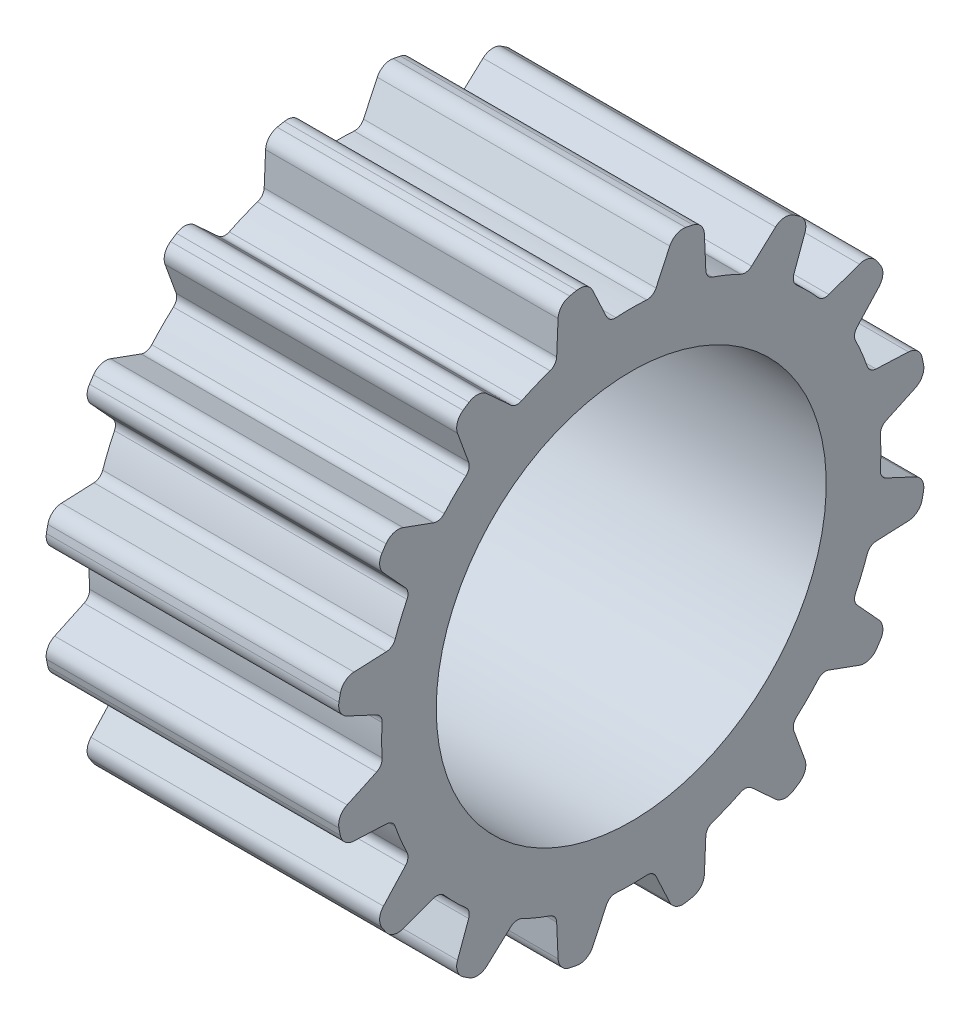
SolidWorks part; units mm, degrees
ref_plane "Front" through (0, 0, 0) normal (0, 0, 1) x (1, 0, 0)
ref_plane "Top" through (0, 0, 0) normal (0, 1, 0) x (1, 0, 0)
ref_plane "Right" through (0, 0, 0) normal (1, 0, 0) x (0, 0, -1)
sketch "Support-Cog" plane through (0, 0, 0) normal (1, 0, 0) x (0, 0, -1)
  line L0 (0, 0) -> (0, 6.1) construction
  line L3 (0.8861, 6.0353) -> (0.45, 5.1)
  line L4 (-0.8861, 6.0353) -> (-0.45, 5.1)
  line L5 (0.45, 5.1) -> (-0.45, 5.1) construction
  circle A1 centre (0, 0) radius 5.1198 construction
  circle A2 centre (0, 0) radius 6.1 construction
  arc A5 (0.7898, 5.8288) -> (1.1166, 5.9969) centre (1.0617, 5.702) cw
  arc A6 (-0.7898, 5.8288) -> (-1.1166, 5.9969) centre (-1.0617, 5.702) ccw
  circle A7 centre (0, 0) radius 4
  arc A8 (0.5084, 5.2252) -> (0.3148, 5.1101) centre (0.3271, 5.3097) cw
  arc A9 (-0.5084, 5.2252) -> (-0.3148, 5.1101) centre (-0.3271, 5.3097) ccw
  dimension "D1" = 50
  dimension "D2" = 0.9
  dimension "Diam-Gear" = 12.2
  dimension "Diam-Hole-Shaft" = 8
  dimension "D4" = 0.3
  dimension "D5" = 0.2
  dimension "D3" = 1
sketch "Support-Front" plane through (0, 0, 0) normal (0, 0, 1) x (1, 0, 0)
  line L0 (0, 0) -> (16, 0) construction
  line L1 (0, -4) -> (16, -4)
  line L2 (16, -8) -> (16, 8)
  line L3 (16, 8) -> (6, 8)
  line L4 (6, 8) -> (6, 6.1)
  line L5 (6, 6.1) -> (0, 6.1)
  line L6 (0, 6.1) -> (0, -6.1)
  line L7 (3, 6.1) -> (3, 0) construction
  line L8 (6, -6.1) -> (0, -6.1)
  line L9 (6, 8) -> (6, -8) construction
  line L10 (16, -8) -> (6, -8)
  line L11 (0, 6.1) -> (0, 8)
  line L12 (0, 4) -> (16, 4)
  line L13 (6, 6.1) -> (6, 8)
  line L14 (-0.3806, 7.8706) -> (0, 6.4501)
  line L15 (6, -8) -> (6, -6.1)
  line L16 (6, -6.1) -> (6, -8)
  line L17 (0, 6.4501) -> (0, 2.5423)
  line L18 (0.5, 2.5423) -> (0, 2.5423)
  line L19 (6, 2.5423) -> (6, 6.1)
  line L20 (0, -2.5423) -> (0, -6.1)
  line L21 (5.5, 6.5159) -> (5.5, 6.4501)
  line L22 (0, 2.5423) -> (0, 6.1)
  line L23 (6, -6.1) -> (6, -8)
  line L24 (6.3806, 7.8706) -> (5.8977, 8)
  line L25 (6, -8) -> (6, -6.1)
  line L26 (5.8977, 8) -> (5.5, 6.5159)
  line L27 (0.5, 2.5423) -> (0.5, 6.4501)
  line L28 (0.5, 6.4501) -> (0, 6.1) construction
  line L29 (6, 6.1) -> (6, 8)
  line L30 (0.5, 2.5423) -> (0, 6.1) construction
  line L31 (0, 6.4501) -> (0.5, 6.4501) construction
  line L34 (6, 6.4501) -> (5.5, 6.4501) construction
  line L35 (5.5, 2.5423) -> (5.5, 6.4501)
  line L36 (6, -2.5423) -> (6, -6.1)
  line L37 (6, 2.5423) -> (6, 6.1)
  line L38 (5.5, 2.5423) -> (6, 2.5423)
  line L39 (0.1023, 8) -> (0.5, 6.5159)
  line L40 (6, 6.4501) -> (6, 2.5423)
  line L41 (-0.3806, 7.8706) -> (0.1023, 8)
  line L42 (6.3806, 7.8706) -> (6, 6.4501)
  line L43 (6, 6.1) -> (6, 8)
  line L44 (0.5, -6.5159) -> (0.5, -6.4501)
  line L45 (6, -6.1) -> (6, -8)
  line L46 (6.3806, -7.8706) -> (6, -6.4501)
  line L47 (-0.3806, -7.8706) -> (0.1023, -8)
  line L48 (6, -6.4501) -> (6, -2.5423)
  line L49 (0.5, 6.5159) -> (0.5, 6.4501)
  line L50 (0.1023, -8) -> (0.5, -6.5159)
  line L51 (5.5, -2.5423) -> (6, -2.5423)
  line L52 (6, -2.5423) -> (6, -6.1)
  line L53 (5.5, -2.5423) -> (5.5, -6.4501)
  line L54 (6, -6.4501) -> (5.5, -6.4501) construction
  line L55 (0, -6.4501) -> (0.5, -6.4501) construction
  line L56 (6, -6.1) -> (6, -8)
  line L57 (0.5, -2.5423) -> (0.5, -6.4501)
  line L58 (5.8977, -8) -> (5.5, -6.5159)
  line L59 (6.3806, -7.8706) -> (5.8977, -8)
  line L60 (0, -2.5423) -> (0, -6.1)
  line L61 (5.5, -6.5159) -> (5.5, -6.4501)
  line L62 (6, -2.5423) -> (6, -6.1)
  line L63 (0.5, -2.5423) -> (0, -2.5423)
  line L64 (0, -6.4501) -> (0, -2.5423)
  line L65 (-0.3806, -7.8706) -> (0, -6.4501)
  line L66 (6, -6.1) -> (6, -8)
  line L67 (0, -6.1) -> (0, -8)
  line L68 (6, -6.1) -> (0, -6.1)
  line L69 (6, -8) -> (6, -6.1)
  line L70 (0, 6.4501) -> (0.5, 6.5159) construction
  dimension "D1" = 55
  dimension "Diam-Hub" = 16
  dimension "D2" = 8
  dimension "D3" = 15
  dimension "Width-Total" = 16
  dimension "Width-Cog" = 6
  dimension "Thickn-Flange" = 0.5
  dimension "Diam-Flange" = 16
sketch "Support-Key" plane through (0, 0, 0) normal (1, 0, 0) x (0, 0, -1)
  line L0 (0, -4) -> (0, 196) construction
  line L1 (0, 0) -> (0, 6.1) construction
  line L2 (1, 196) -> (-1, 196)
  line L3 (-1, 196) -> (-1, 0)
  line L4 (1, 196) -> (1, 0)
  line L5 (-1, 0) -> (1, 0)
  circle A0 centre (0, 0) radius 4 construction
  point P12 (0, 0)
  dimension "Height-Key" = 200
  dimension "Width-Key" = 2
sketch "Support-Stop-Screw" plane through (0, 0, 0) normal (0, 0, 1) x (1, 0, 0)
  line L0 (11, 0) -> (11, 196) construction
  line L1 (0, 0) -> (16, 0) construction
  line L2 (0, 0) -> (0, 6.1) construction
  line L3 (12, 196) -> (0, 196) construction
  line L4 (10, 196) -> (12, 196)
  line L5 (12, 196) -> (12, 0)
  line L6 (10, 196) -> (10, 0)
  line L7 (12, 0) -> (10, 0)
  line L8 (0, -4) -> (0, 196) construction
  dimension "Dist-Hole-Stop-Screw" = 11
  dimension "Diam-Stop-Screw" = 2
sketch "Sketch2" plane through (0, 0, 0) normal (0, 0, 1) x (1, 0, 0)
  line L5 (0, 0) -> (16, 0) construction
  line L10 (6, 6.1) -> (0, 6.1) construction
  line L11 (0, 0) -> (0, 6.1) construction
  line L12 (0, 0) -> (6, 0)
  line L13 (6, 0) -> (6, 6.1)
  line L15 (6, 6.1) -> (0, 6.1)
  line L16 (0, 0) -> (0, 6.1)
  line L17 (0, 0) -> (16, 0) construction
revolve "Body" add sketch "Sketch2" angle 360 about L17
sketch "Sketch6" plane through (0, 0, 0) normal (1, 0, 0) x (0, 0, -1)
  line L0 (0.8861, 6.0353) -> (0.45, 5.1) construction
  line L1 (-0.8861, 6.0353) -> (-0.45, 5.1) construction
  line L2 (0.7898, 5.8288) -> (0.5084, 5.2252)
  line L3 (-0.7898, 5.8288) -> (-0.5084, 5.2252)
  arc A0 (0.3148, 5.1101) -> (0.5084, 5.2252) centre (0.3271, 5.3097) ccw construction
  circle A1 centre (0, 0) radius 5.1198 construction
  arc A2 (-0.5084, 5.2252) -> (-0.3148, 5.1101) centre (-0.3271, 5.3097) ccw construction
  arc A3 (-0.7898, 5.8288) -> (-1.1166, 5.9969) centre (-1.0617, 5.702) ccw construction
  circle A4 centre (0, 0) radius 6.1 construction
  arc A5 (1.1166, 5.9969) -> (0.7898, 5.8288) centre (1.0617, 5.702) ccw construction
  arc A6 (0.3148, 5.1101) -> (0.5084, 5.2252) centre (0.3271, 5.3097) ccw
  arc A7 (0.3148, 5.1101) -> (-0.3148, 5.1101) centre (0, 0) ccw
  arc A8 (-0.5084, 5.2252) -> (-0.3148, 5.1101) centre (-0.3271, 5.3097) ccw
  arc A9 (-0.7898, 5.8288) -> (-1.1166, 5.9969) centre (-1.0617, 5.702) ccw
  arc A10 (1.1166, 5.9969) -> (-1.1166, 5.9969) centre (0, 0) ccw
  arc A11 (1.1166, 5.9969) -> (0.7898, 5.8288) centre (1.0617, 5.702) ccw
extrude "Cog" cut sketch "Sketch6" along normal through all
pattern_circular "Pattern-Cog" count 16 over 360 about axis through (0, 0, 0) along (1, 0, 0) of "Cog"
sketch "Sketch3" plane through (0, 0, 0) normal (0, 0, 1) x (1, 0, 0)
  line L2 (16, 8) -> (6, 8) construction
  line L3 (16, -8) -> (16, 8) construction
  line L4 (6, 0) -> (16, 0)
  line L5 (16, 8) -> (6, 8)
  line L6 (6, 8) -> (6, 0)
  line L7 (0, 0) -> (16, 0) construction
  line L8 (0, 0) -> (16, 0) construction
  line L10 (16, 0) -> (16, 8)
revolve "Hub" [suppressed] add sketch "Sketch3" angle 360 about L8
sketch "Sketch15" plane through (0, 0, 0) normal (0, 0, 1) x (1, 0, 0)
  line L0 (11, 196) -> (11, 0) construction
  line L1 (11, 196) -> (12, 196)
  line L2 (12, 196) -> (12, 0)
  line L3 (12, 0) -> (11, 0)
  line L4 (11, 196) -> (11, 0)
revolve "Stop-Screw" [suppressed] cut sketch "Sketch15" angle 360 about L0
sketch "Sketch16" plane through (0, 0, 0) normal (0, 0, 1) x (1, 0, 0)
  line L0 (-0.3806, 7.8706) -> (-0.3806, 2.5423)
  line L2 (1.4261, 2.5423) -> (1.4261, 3.0595)
  line L7 (0.1023, 8) -> (0.5, 6.5159) construction
  line L10 (-0.3806, 7.8706) -> (0.1023, 8) construction
  line L11 (1.4261, 2.5423) -> (-0.3806, 2.5423)
  line L12 (0, 0) -> (16, 0) construction
  line L13 (0, 0) -> (16, 0) construction
  line L16 (0.1023, 8) -> (1.4261, 3.0595)
  line L19 (-0.3806, 7.8706) -> (0.1023, 8)
revolve "Flange-Left" [suppressed] add sketch "Sketch16" angle 360 about L13
sketch "Sketch17" plane through (0, 0, 0) normal (0, 0, 1) x (1, 0, 0)
  line L0 (0, 0) -> (16, 0) construction
  line L2 (6.3806, 7.8706) -> (5.8977, 8) construction
  line L3 (5.8977, 8) -> (5.5, 6.5159) construction
  line L4 (6.3806, 7.8706) -> (6.3806, 2.5423)
  line L5 (0, 0) -> (9, 0) construction
  line L6 (6.9067, 2.5423) -> (6.9067, 11.7658)
  line L11 (5.5, 2.5423) -> (6, 2.5423) construction
  line L14 (6.3806, 7.8706) -> (5.8977, 8)
  line L15 (5.8977, 8) -> (6.9067, 11.7658)
  line L18 (6.9067, 2.5423) -> (6.3806, 2.5423)
revolve "Flange-Right" [suppressed] add sketch "Sketch17" angle 360 about L5
sketch "Sketch8" plane through (0, 0, 0) normal (0, 0, 1) x (1, 0, 0)
  line L0 (16, -8) -> (16, 8) construction
  line L3 (16, 0) -> (16, -4)
  line L4 (-1.304, -4) -> (-1.304, 0)
  line L5 (-1.304, -4) -> (16, -4)
  line L6 (0, 0) -> (16, 0) construction
  line L7 (-1.304, 0) -> (16, 0) construction
  line L8 (-1.304, 0) -> (16, 0)
revolve "Hole-Shaft" cut sketch "Sketch8" angle 360 about L7
sketch "Sketch11" plane through (0, 0, 0) normal (1, 0, 0) x (0, 0, -1)
  line L4 (1, 196) -> (-1, 196)
  line L5 (-1, 196) -> (-1, 0)
  line L6 (-1, 0) -> (1, 0)
  line L7 (1, 0) -> (1, 196)
  line L8 (1, 196) -> (-1, 196)
  line L9 (-1, 196) -> (-1, 0)
  line L10 (-1, 0) -> (1, 0)
  line L11 (1, 0) -> (1, 196)
  dimension "D1" = 0
extrude "Key" [suppressed] cut sketch "Sketch11" along normal through all
pattern_circular "Pattern-Stop-Screw" [suppressed] count 2 every 90 about axis through (0, 0, 0) along (1, 0, 0)
equation "\"Dist-Hole-Stop-Screw@Support-Stop-Screw\"=\"Width-Cog@Support-Front\"+(\"Width-Total@Support-Front\"-\"Width-Cog@Support-Front\")/2"
